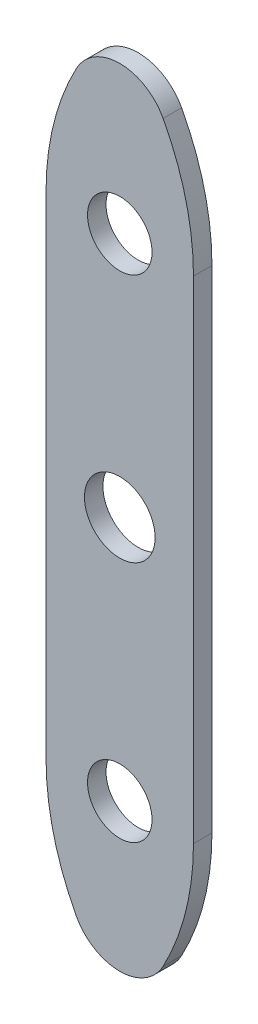
SolidWorks part; units mm, degrees
ref_plane "front" through (0, 0, 0) normal (0, 0, 1) x (1, 0, 0)
ref_plane "top" through (0, 0, 0) normal (0, 1, 0) x (1, 0, 0)
ref_plane "right" through (0, 0, 0) normal (1, 0, 0) x (0, 0, -1)
sketch "Sketch1" plane through (0, 0, 0) normal (0, 0, 1) x (1, 0, 0)
  line L0 (0, 101.6) -> (0, -101.6) construction
  line L1 (19.05, 63.5) -> (19.05, -63.5)
  line L2 (-19.05, 63.5) -> (-19.05, -63.5)
  arc A0 (-19.05, -63.5) -> (-11.2059, -94.8765) centre (47.625, -63.5) ccw
  arc A1 (11.2059, 94.8765) -> (-11.2059, 94.8765) centre (0, 88.9) ccw
  arc A2 (-11.2059, -94.8765) -> (11.2059, -94.8765) centre (0, -88.9) ccw
  arc A3 (-19.05, 63.5) -> (-11.2059, 94.8765) centre (47.625, 63.5) cw
  circle A4 centre (0, 0) radius 19.05 construction
  circle A5 centre (0, 0) radius 9.1281
  circle A6 centre (0, -63.5) radius 8.3344
  circle A7 centre (0, 63.5) radius 8.3344
  arc A8 (19.05, 63.5) -> (11.2059, 94.8765) centre (-47.625, 63.5) ccw
  arc A9 (19.05, -63.5) -> (11.2059, -94.8765) centre (-47.625, -63.5) cw
  dimension "D1" = 38.1
  dimension "D2" = 12.7
  dimension "D3" = 18.2562
  dimension "D5" = 63.5
  dimension "D9" = 16.6687
  dimension "D4" = 203.2
  dimension "D6" = 63.5
  dimension "D7" = 88.9
  dimension "D8" = 38.1
extrude "Base-Extrude" add sketch "Sketch1" along normal blind 4.7752
